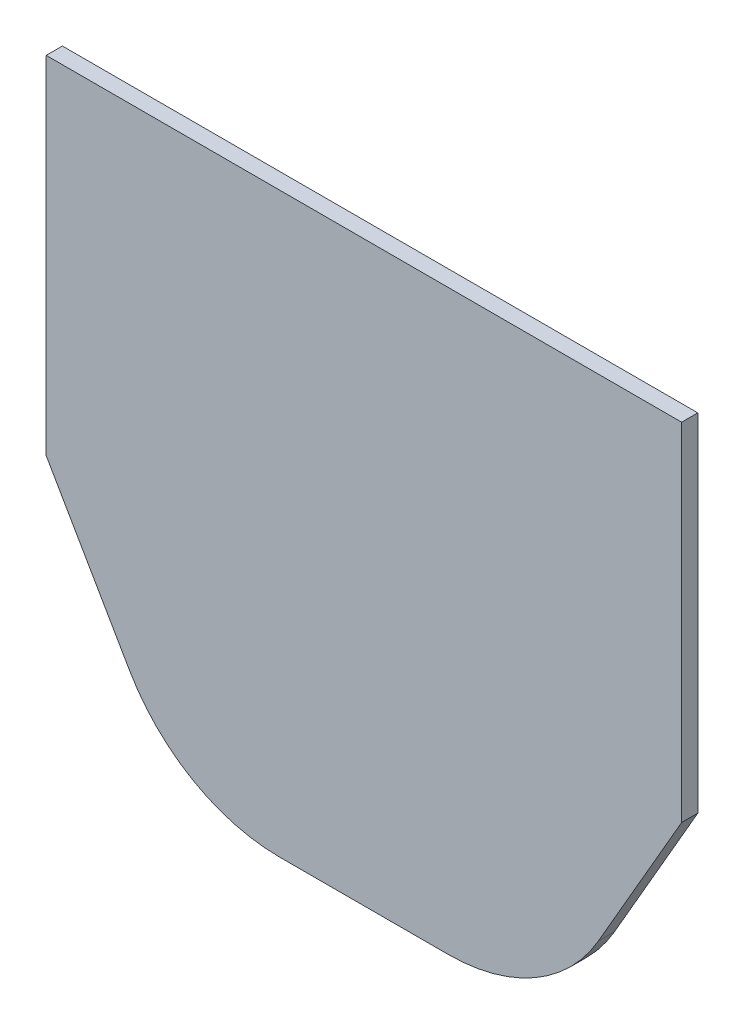
SolidWorks part; units mm, degrees
material "Plain Carbon Steel"
ref_plane "Front Plane" through (0, 0, 0) normal (0, 0, 1) x (1, 0, 0)
ref_plane "Top Plane" through (0, 0, 0) normal (0, 1, 0) x (1, 0, 0)
ref_plane "Right Plane" through (0, 0, 0) normal (1, 0, 0) x (0, 0, -1)
sketch "Sketch1" plane through (0, 0, 0) normal (0, 0, 1) x (1, 0, 0)
  line L0 (-161.4995, 280.5616) -> (-161.4995, 356.7886)
  line L1 (-161.4995, 280.5616) -> (-179.8149, 248.8386)
  line L2 (-301.1995, 280.5616) -> (-301.1995, 356.7886)
  line L3 (-301.1995, 280.5616) -> (-282.8842, 248.8386)
  line L4 (-161.4995, 356.7886) -> (-301.1995, 356.7886)
  line L5 (-249.8886, 229.7886) -> (-212.8104, 229.7886)
  arc A0 (-282.8842, 248.8386) -> (-249.8886, 229.7886) centre (-249.8886, 267.8886) ccw
  arc A1 (-212.8104, 229.7886) -> (-179.8149, 248.8386) centre (-212.8104, 267.8886) ccw
  circle A2 centre (-263.0995, 338.6084) radius 2.0193
  circle A3 centre (-268.9415, 338.6084) radius 1.9812
  circle A4 centre (-270.0845, 249.7084) radius 2.0193
  circle A5 centre (-275.9265, 249.7084) radius 1.9812
  circle A6 centre (-199.5995, 338.6084) radius 2.0193
  circle A7 centre (-193.7575, 338.6084) radius 1.9812
  circle A8 centre (-192.6145, 249.7084) radius 2.0193
  circle A9 centre (-186.7725, 249.7084) radius 1.9812
  circle A10 centre (-231.3495, 268.0205) radius 14.2875
  circle A11 centre (-231.3495, 308.7367) radius 11.1125
extrude "Boss-Extrude1" add sketch "Sketch1" against normal blind 3.556 contours L2 L4 L0 L1 A1 L5 A0 L3
sketch "Sketch5" plane through (0, 0, 0) normal (0, 0, 1) x (1, 0, 0)
  circle A0 centre (-231.3495, 268.0205) radius 14.2875
sketch "Sketch6" plane through (0, 0, 0) normal (0, 0, 1) x (1, 0, 0)
  circle A0 centre (-231.3495, 308.7367) radius 11.1125
sketch "Sketch7" plane through (0, 0, 0) normal (0, 0, 1) x (1, 0, 0)
  circle A0 centre (-270.0845, 249.7084) radius 2.0193
  circle A1 centre (-275.9265, 249.7084) radius 1.9812
  circle A2 centre (-192.6145, 249.7084) radius 2.0193
  circle A3 centre (-186.7725, 249.7084) radius 1.9812
sketch "Sketch8" plane through (0, 0, 0) normal (0, 0, 1) x (1, 0, 0)
  circle A0 centre (-263.0995, 338.6084) radius 2.0193
  circle A1 centre (-268.9415, 338.6084) radius 1.9812
  circle A2 centre (-199.5995, 338.6084) radius 2.0193
  circle A3 centre (-193.7575, 338.6084) radius 1.9812
